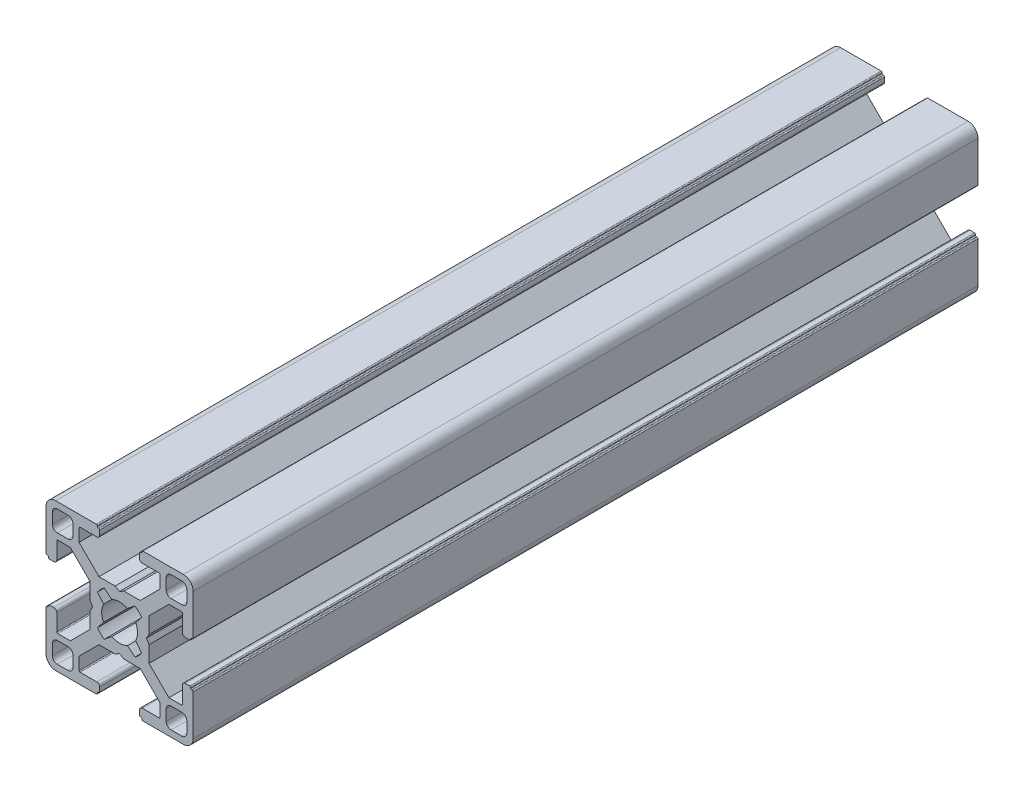
SolidWorks part; units mm, degrees
ref_plane "Front" through (0, 0, 0) normal (0, 0, 1) x (1, 0, 0)
ref_plane "Top" through (0, 0, 0) normal (0, 1, 0) x (1, 0, 0)
ref_plane "Right" through (0, 0, 0) normal (1, 0, 0) x (0, 0, -1)
sketch "Sketch1" plane through (0, 0, 0) normal (0, 0, 1) x (1, 0, 0)
  line L0 (13.7, 12.7) -> (13.7, 10.5)
  line L1 (10.5, 9.5) -> (12.7, 9.5)
  line L2 (9.5, 12.7) -> (9.5, 10.5)
  line L3 (10.5, 13.7) -> (12.7, 13.7)
  line L4 (3.1359, 4.5184) -> (1.6001, 3.2806)
  line L5 (3.2806, 1.6001) -> (4.5053, 3.1547)
  line L6 (6.0045, 0.9) -> (5.4849, 0)
  line L7 (6.0045, 4.2045) -> (6.0045, 0.9)
  line L8 (0, -5.4849) -> (0.9, -6)
  line L9 (0.9, -6) -> (4.2045, -6)
  line L10 (4.2045, -6) -> (8.25, -10.05)
  line L11 (8.25, -10.05) -> (8.25, -12.6)
  line L12 (4.65, -12.8) -> (8.05, -12.8)
  line L13 (4.05, -14.3) -> (4.05, -13.4)
  line L14 (4.25, -14.5) -> (4.35, -14.5)
  line L15 (4.55, -14.8) -> (4.55, -14.7)
  line L16 (4.75, -15) -> (13, -15)
  line L17 (15, -13) -> (15, -4.75)
  line L18 (14.7, -4.55) -> (14.8, -4.55)
  line L19 (14.5, -4.35) -> (14.5, -4.25)
  line L20 (13.4, -4.05) -> (14.3, -4.05)
  line L21 (12.8, -8.05) -> (12.8, -4.65)
  line L22 (12.6, -8.25) -> (10.05, -8.25)
  line L23 (10.05, -8.25) -> (6.0045, -4.2045)
  line L24 (6.0045, -4.2045) -> (6.0045, -0.9)
  line L25 (6.0045, -0.9) -> (5.4849, 0)
  line L26 (10.05, 8.25) -> (6.0045, 4.2045)
  line L27 (12.6, 8.25) -> (10.05, 8.25)
  line L28 (12.8, 8.05) -> (12.8, 4.65)
  line L29 (13.4, 4.05) -> (14.3, 4.05)
  line L30 (14.5, 4.35) -> (14.5, 4.25)
  line L31 (14.7, 4.55) -> (14.8, 4.55)
  line L32 (15, 13) -> (15, 4.75)
  line L33 (4.75, 15) -> (13, 15)
  line L34 (4.55, 14.8) -> (4.55, 14.7)
  line L35 (4.25, 14.5) -> (4.35, 14.5)
  line L36 (4.05, 14.3) -> (4.05, 13.4)
  line L37 (4.65, 12.8) -> (8.05, 12.8)
  line L38 (8.25, 10.05) -> (8.25, 12.6)
  line L39 (4.2045, 6) -> (8.25, 10.05)
  line L40 (0.9, 6) -> (4.2045, 6)
  line L41 (0, 5.4849) -> (0.9, 6)
  line L42 (-13.7, -12.7) -> (-13.7, -10.5)
  line L43 (-10.5, -9.5) -> (-12.7, -9.5)
  line L44 (-9.5, -12.7) -> (-9.5, -10.5)
  line L45 (-10.5, -13.7) -> (-12.7, -13.7)
  line L46 (-3.1359, -4.5184) -> (-1.6001, -3.2806)
  line L47 (-3.2806, -1.6001) -> (-4.5053, -3.1547)
  line L48 (0, 5.4849) -> (-0.9, 6)
  line L49 (-0.9, 6) -> (-4.2045, 6)
  line L50 (-4.2045, 6) -> (-8.25, 10.05)
  line L51 (-8.25, 10.05) -> (-8.25, 12.6)
  line L52 (-4.65, 12.8) -> (-8.05, 12.8)
  line L53 (-4.05, 14.3) -> (-4.05, 13.4)
  line L54 (-4.25, 14.5) -> (-4.35, 14.5)
  line L55 (-4.55, 14.8) -> (-4.55, 14.7)
  line L56 (-4.75, 15) -> (-13, 15)
  line L57 (-15, 13) -> (-15, 4.75)
  line L58 (-14.7, 4.55) -> (-14.8, 4.55)
  line L59 (-14.5, 4.35) -> (-14.5, 4.25)
  line L60 (-13.4, 4.05) -> (-14.3, 4.05)
  line L61 (-12.8, 8.05) -> (-12.8, 4.65)
  line L62 (-12.6, 8.25) -> (-10.05, 8.25)
  line L63 (-10.05, 8.25) -> (-6.0045, 4.2045)
  line L64 (-6.0045, -0.9) -> (-5.4849, 0)
  line L65 (-6.0045, -4.2045) -> (-6.0045, -0.9)
  line L66 (-10.05, -8.25) -> (-6.0045, -4.2045)
  line L67 (-12.6, -8.25) -> (-10.05, -8.25)
  line L68 (-12.8, -8.05) -> (-12.8, -4.65)
  line L69 (-13.4, -4.05) -> (-14.3, -4.05)
  line L70 (-14.5, -4.35) -> (-14.5, -4.25)
  line L71 (-14.7, -4.55) -> (-14.8, -4.55)
  line L72 (-15, -13) -> (-15, -4.75)
  line L73 (-4.75, -15) -> (-13, -15)
  line L74 (-4.55, -14.8) -> (-4.55, -14.7)
  line L75 (-4.25, -14.5) -> (-4.35, -14.5)
  line L76 (-4.05, -14.3) -> (-4.05, -13.4)
  line L77 (3.2806, -1.6001) -> (4.5053, -3.1547)
  line L78 (3.1359, -4.5184) -> (1.6001, -3.2806)
  line L79 (-4.65, -12.8) -> (-8.05, -12.8)
  line L80 (-8.25, -10.05) -> (-8.25, -12.6)
  line L81 (-4.2045, -6) -> (-8.25, -10.05)
  line L82 (-0.9, -6) -> (-4.2045, -6)
  line L83 (0, -5.4849) -> (-0.9, -6)
  line L84 (10.5, -13.7) -> (12.7, -13.7)
  line L85 (9.5, -12.7) -> (9.5, -10.5)
  line L86 (10.5, -9.5) -> (12.7, -9.5)
  line L87 (13.7, -12.7) -> (13.7, -10.5)
  line L88 (-6.0045, 4.2045) -> (-6.0045, 0.9)
  line L89 (-6.0045, 0.9) -> (-5.4849, 0)
  line L90 (-3.2806, 1.6001) -> (-4.5053, 3.1547)
  line L91 (-3.1359, 4.5184) -> (-1.6001, 3.2806)
  line L92 (-10.5, 13.7) -> (-12.7, 13.7)
  line L93 (-9.5, 12.7) -> (-9.5, 10.5)
  line L94 (-10.5, 9.5) -> (-12.7, 9.5)
  line L95 (-13.7, 12.7) -> (-13.7, 10.5)
  line L96 (-23.4857, 0) -> (20.9308, 0) construction
  line L97 (0, 17.9563) -> (0, -17.361) construction
  arc A0 (13.7, 12.7) -> (12.7, 13.7) centre (12.7, 12.7) ccw
  arc A1 (12.7, 9.5) -> (13.7, 10.5) centre (12.7, 10.5) ccw
  arc A2 (9.5, 10.5) -> (10.5, 9.5) centre (10.5, 10.5) ccw
  arc A3 (10.5, 13.7) -> (9.5, 12.7) centre (10.5, 12.7) ccw
  arc A4 (1.6001, 3.2806) -> (-1.6001, 3.2806) centre (0, 0) ccw
  arc A5 (8.25, -12.6) -> (8.05, -12.8) centre (8.05, -12.6) cw
  arc A6 (4.65, -12.8) -> (4.05, -13.4) centre (4.65, -13.4) ccw
  arc A7 (4.05, -14.3) -> (4.25, -14.5) centre (4.25, -14.3) ccw
  arc A8 (4.35, -14.5) -> (4.55, -14.7) centre (4.35, -14.7) cw
  arc A9 (4.55, -14.8) -> (4.75, -15) centre (4.75, -14.8) ccw
  arc A10 (13, -15) -> (15, -13) centre (13, -13) ccw
  arc A11 (15, -4.75) -> (14.8, -4.55) centre (14.8, -4.75) ccw
  arc A12 (14.7, -4.55) -> (14.5, -4.35) centre (14.7, -4.35) cw
  arc A13 (14.5, -4.25) -> (14.3, -4.05) centre (14.3, -4.25) ccw
  arc A14 (13.4, -4.05) -> (12.8, -4.65) centre (13.4, -4.65) ccw
  arc A15 (12.8, -8.05) -> (12.6, -8.25) centre (12.6, -8.05) cw
  arc A16 (4.5053, 3.1547) -> (3.1359, 4.5184) centre (0, 0) ccw
  arc A17 (12.8, 8.05) -> (12.6, 8.25) centre (12.6, 8.05) ccw
  arc A18 (13.4, 4.05) -> (12.8, 4.65) centre (13.4, 4.65) cw
  arc A19 (14.5, 4.25) -> (14.3, 4.05) centre (14.3, 4.25) cw
  arc A20 (14.7, 4.55) -> (14.5, 4.35) centre (14.7, 4.35) ccw
  arc A21 (15, 4.75) -> (14.8, 4.55) centre (14.8, 4.75) cw
  arc A22 (13, 15) -> (15, 13) centre (13, 13) cw
  arc A23 (4.55, 14.8) -> (4.75, 15) centre (4.75, 14.8) cw
  arc A24 (4.35, 14.5) -> (4.55, 14.7) centre (4.35, 14.7) ccw
  arc A25 (4.05, 14.3) -> (4.25, 14.5) centre (4.25, 14.3) cw
  arc A26 (4.65, 12.8) -> (4.05, 13.4) centre (4.65, 13.4) cw
  arc A27 (8.25, 12.6) -> (8.05, 12.8) centre (8.05, 12.6) ccw
  arc A28 (-13.7, -12.7) -> (-12.7, -13.7) centre (-12.7, -12.7) ccw
  arc A29 (-12.7, -9.5) -> (-13.7, -10.5) centre (-12.7, -10.5) ccw
  arc A30 (-9.5, -10.5) -> (-10.5, -9.5) centre (-10.5, -10.5) ccw
  arc A31 (-10.5, -13.7) -> (-9.5, -12.7) centre (-10.5, -12.7) ccw
  arc A32 (-4.5053, -3.1547) -> (-3.1359, -4.5184) centre (0, 0) ccw
  arc A33 (-3.2806, 1.6001) -> (-3.2806, -1.6001) centre (0, 0) ccw
  arc A34 (-8.25, 12.6) -> (-8.05, 12.8) centre (-8.05, 12.6) cw
  arc A35 (-4.65, 12.8) -> (-4.05, 13.4) centre (-4.65, 13.4) ccw
  arc A36 (-4.05, 14.3) -> (-4.25, 14.5) centre (-4.25, 14.3) ccw
  arc A37 (-4.35, 14.5) -> (-4.55, 14.7) centre (-4.35, 14.7) cw
  arc A38 (-4.55, 14.8) -> (-4.75, 15) centre (-4.75, 14.8) ccw
  arc A39 (-13, 15) -> (-15, 13) centre (-13, 13) ccw
  arc A40 (-15, 4.75) -> (-14.8, 4.55) centre (-14.8, 4.75) ccw
  arc A41 (-14.7, 4.55) -> (-14.5, 4.35) centre (-14.7, 4.35) cw
  arc A42 (-14.5, 4.25) -> (-14.3, 4.05) centre (-14.3, 4.25) ccw
  arc A43 (-13.4, 4.05) -> (-12.8, 4.65) centre (-13.4, 4.65) ccw
  arc A44 (-12.8, 8.05) -> (-12.6, 8.25) centre (-12.6, 8.05) cw
  arc A45 (-4.5053, 3.1547) -> (-3.1359, 4.5184) centre (0, 0) cw
  arc A46 (-12.8, -8.05) -> (-12.6, -8.25) centre (-12.6, -8.05) ccw
  arc A47 (-13.4, -4.05) -> (-12.8, -4.65) centre (-13.4, -4.65) cw
  arc A48 (-14.5, -4.25) -> (-14.3, -4.05) centre (-14.3, -4.25) cw
  arc A49 (3.2806, 1.6001) -> (3.2806, -1.6001) centre (0, 0) cw
  arc A50 (4.5053, -3.1547) -> (3.1359, -4.5184) centre (0, 0) cw
  arc A51 (1.6001, -3.2806) -> (-1.6001, -3.2806) centre (0, 0) cw
  arc A52 (-14.7, -4.55) -> (-14.5, -4.35) centre (-14.7, -4.35) ccw
  arc A53 (-15, -4.75) -> (-14.8, -4.55) centre (-14.8, -4.75) cw
  arc A54 (-13, -15) -> (-15, -13) centre (-13, -13) cw
  arc A55 (-4.55, -14.8) -> (-4.75, -15) centre (-4.75, -14.8) cw
  arc A56 (10.5, -13.7) -> (9.5, -12.7) centre (10.5, -12.7) cw
  arc A57 (9.5, -10.5) -> (10.5, -9.5) centre (10.5, -10.5) cw
  arc A58 (12.7, -9.5) -> (13.7, -10.5) centre (12.7, -10.5) cw
  arc A59 (13.7, -12.7) -> (12.7, -13.7) centre (12.7, -12.7) cw
  arc A60 (-4.35, -14.5) -> (-4.55, -14.7) centre (-4.35, -14.7) ccw
  arc A61 (-4.05, -14.3) -> (-4.25, -14.5) centre (-4.25, -14.3) cw
  arc A62 (-4.65, -12.8) -> (-4.05, -13.4) centre (-4.65, -13.4) cw
  arc A63 (-8.25, -12.6) -> (-8.05, -12.8) centre (-8.05, -12.6) ccw
  arc A64 (-10.5, 13.7) -> (-9.5, 12.7) centre (-10.5, 12.7) cw
  arc A65 (-9.5, 10.5) -> (-10.5, 9.5) centre (-10.5, 10.5) cw
  arc A66 (-12.7, 9.5) -> (-13.7, 10.5) centre (-12.7, 10.5) cw
  arc A67 (-13.7, 12.7) -> (-12.7, 13.7) centre (-12.7, 12.7) cw
  point P81 (15, 15)
  point P82 (0, 15)
  point P203 (0, -15)
  point P204 (15, -15)
  point P206 (0, 0)
  point P207 (15, 0)
  point P219 (-15, 0)
  point P220 (-15, -15)
  point P221 (-15, 15)
  dimension "D6" = 7.3
  dimension "D7" = 11
  dimension "D1" = 30
  dimension "D2" = 15
  dimension "D3" = 30
  dimension "D4" = 8.1
  dimension "D5" = 9
  dimension "D8" = 8.1
extrude "Base-Extrude" add sketch "Sketch1" against normal blind 160
